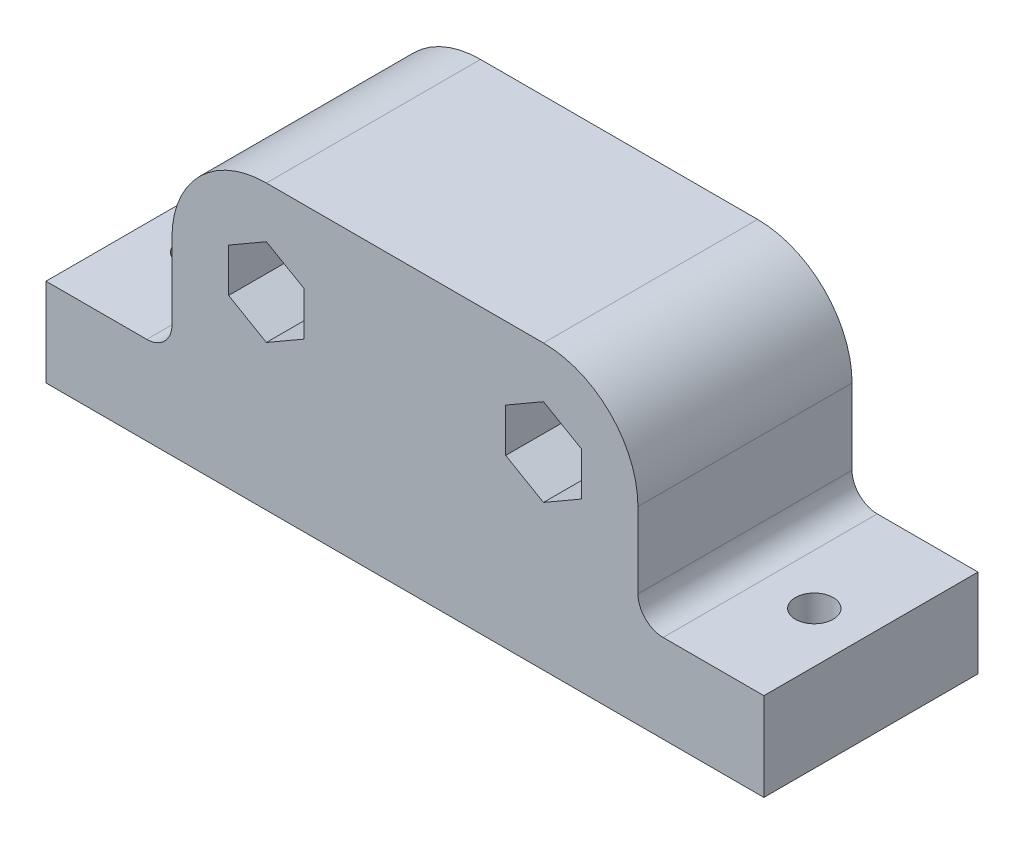
SolidWorks part; units mm, degrees
ref_plane "Front" through (0, 0, 0) normal (0, 0, 1) x (1, 0, 0)
ref_plane "Top" through (0, 0, 0) normal (0, 1, 0) x (1, 0, 0)
ref_plane "Right" through (0, 0, 0) normal (1, 0, 0) x (0, 0, -1)
sketch "草图1" plane through (0, 0, 0) normal (0, 0, 1) x (1, 0, 0)
  line L0 (0, 0) -> (22, 0) construction
  line L1 (-7.5, 0) -> (-7.5, -8)
  line L2 (0, 7.5) -> (22, 7.5)
  line L3 (0, -7.5) -> (22, -7.5)
  line L4 (0, 3.4641) -> (-3, 1.7321)
  line L5 (-3, 1.7321) -> (-3, -1.7321)
  line L6 (-3, -1.7321) -> (0, -3.4641)
  line L7 (0, -3.4641) -> (3, -1.7321)
  line L8 (3, -1.7321) -> (3, 1.7321)
  line L9 (3, 1.7321) -> (0, 3.4641)
  line L10 (22, 3.4641) -> (19, 1.7321)
  line L11 (19, 1.7321) -> (19, -1.7321)
  line L12 (19, -1.7321) -> (22, -3.4641)
  line L13 (22, -3.4641) -> (25, -1.7321)
  line L14 (25, -1.7321) -> (25, 1.7321)
  line L15 (25, 1.7321) -> (22, 3.4641)
  line L16 (29.5, 0) -> (29.5, -8)
  line L17 (-7.5, -8) -> (-17.5, -8)
  line L18 (-17.5, -8) -> (-17.5, -15)
  line L19 (-17.5, -15) -> (39.5, -15)
  line L20 (39.5, -15) -> (39.5, -8)
  line L21 (39.5, -8) -> (29.5, -8)
  line L22 (29.5, -8) -> (29.5621, -8.0971)
  arc A0 (0, 7.5) -> (0, -7.5) centre (0, 0) ccw
  arc A1 (22, -7.5) -> (22, 7.5) centre (22, 0) ccw
  circle A2 centre (0, 0) radius 2
  circle A3 centre (22, 0) radius 2
  circle A4 centre (0, 0) radius 3 construction
  circle A5 centre (22, 0) radius 3 construction
  point P5 (11, 0)
  dimension "D2" = 4
  dimension "D3" = 4
  dimension "D1" = 15
  dimension "D4" = 22
  dimension "D5" = 6
  dimension "D6" = 6
  dimension "D7" = 8
  dimension "D8" = 8
  dimension "D9" = 10
  dimension "D10" = 7
  dimension "D11" = 10
extrude "凸台-拉伸1" add sketch "草图1" along normal blind 15
fillet "圆角1" radius 2 2 edges at (29.5, -8, 7.5) (-7.5, -8, 7.5)
sketch "草图2" plane through (0, 0, 0) normal (0, 0, -1) x (-1, 0, 0)
  line L8 (-31.5, -8) -> (-39.5, -8)
  line L9 (-39.5, -8) -> (-39.5, -15)
  line L10 (-39.5, -15) -> (17.5, -15)
  line L11 (17.5, -15) -> (17.5, -8)
  line L12 (17.5, -8) -> (9.5, -8)
  line L13 (7.5, -6) -> (7.5, 0)
  line L14 (0, 7.5) -> (-22, 7.5)
  line L15 (-29.5, 0) -> (-29.5, -6)
  line L16 (-31.5, -8) -> (-39.5, -8)
  line L17 (-39.5, -8) -> (-39.5, -15)
  line L18 (-39.5, -15) -> (17.5, -15)
  line L19 (17.5, -15) -> (17.5, -8)
  line L20 (17.5, -8) -> (9.5, -8)
  line L21 (7.5, -6) -> (7.5, 0)
  line L22 (0, 7.5) -> (-22, 7.5)
  line L23 (-29.5, 0) -> (-29.5, -6)
  circle A0 centre (-22, 0) radius 2.5
  circle A1 centre (0, 0) radius 2.5
  arc A8 (7.5, -6) -> (9.5, -8) centre (9.5, -6) ccw
  arc A9 (7.5, 0) -> (0, 7.5) centre (0, 0) ccw
  arc A10 (-22, 7.5) -> (-29.5, 0) centre (-22, 0) ccw
  arc A11 (-31.5, -8) -> (-29.5, -6) centre (-31.5, -6) ccw
  arc A14 (7.5, -6) -> (9.5, -8) centre (9.5, -6) ccw
  arc A15 (7.5, 0) -> (0, 7.5) centre (0, 0) ccw
  arc A16 (-22, 7.5) -> (-29.5, 0) centre (-22, 0) ccw
  arc A17 (-31.5, -8) -> (-29.5, -6) centre (-31.5, -6) ccw
  dimension "D2" = 5
  dimension "D3" = 5
  dimension "D1" = 0
extrude "凸台-拉伸2" add sketch "草图2" along normal blind 2
sketch "草图3" plane through (0, -8, 0) normal (0, 1, 0) x (1, 0, 0)
  line L0 (-13.5, 2) -> (-13.5, -15) construction
  line L1 (-17.5, 2) -> (-9.5, 2) construction
  line L2 (-9.5, -15) -> (-17.5, -15) construction
  line L3 (35.5, 2) -> (35.5, -15) construction
  line L4 (31.5, 2) -> (39.5, 2) construction
  line L5 (39.5, -15) -> (31.5, -15) construction
  circle A0 centre (-13.5, -7) radius 1.5
  circle A1 centre (35.5, -7) radius 1.5
  dimension "D1" = 3
  dimension "D2" = 3
  dimension "D3" = 9
  dimension "D4" = 9
extrude "切除-拉伸1" cut sketch "草图3" against normal through all
